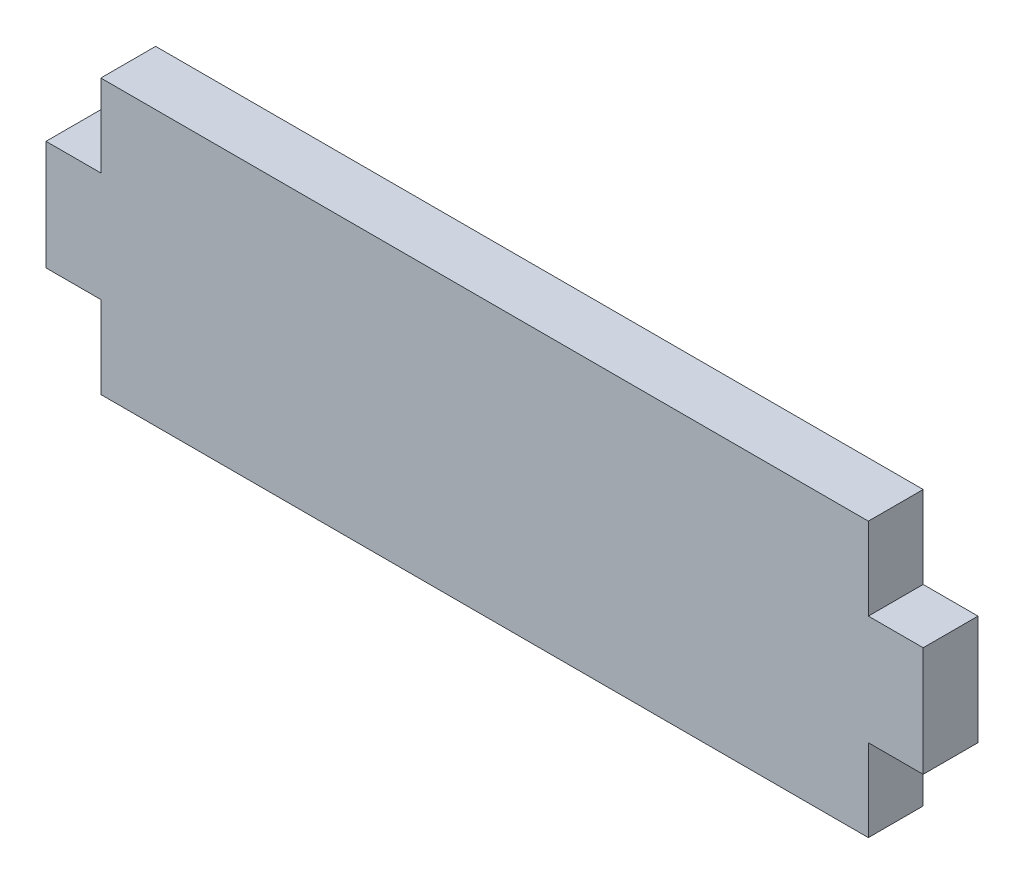
SolidWorks part; units mm, degrees
material "아크릴(내충격성)"
ref_plane "정면" through (0, 0, 0) normal (0, 0, 1) x (1, 0, 0)
ref_plane "윗면" through (0, 0, 0) normal (0, 1, 0) x (1, 0, 0)
ref_plane "우측면" through (0, 0, 0) normal (1, 0, 0) x (0, 0, -1)
sketch "스케치1" plane through (0, 0, 0) normal (0, 0, 1) x (1, 0, 0)
  line L0 (-40, 5) -> (-40, -5)
  line L1 (-35, 12.5) -> (35, 12.5)
  line L2 (-35, 12.5) -> (-35, 5)
  line L3 (-35, -12.5) -> (35, -12.5)
  line L4 (35, 12.5) -> (35, 5)
  line L5 (-35, 12.5) -> (35, -12.5) construction
  line L6 (-35, -12.5) -> (35, 12.5) construction
  line L7 (-35, -5) -> (-35, -12.5)
  line L9 (-40, 5) -> (-35, 5)
  line L10 (-40, -5) -> (-35, -5)
  line L11 (40, -5) -> (35, -5)
  line L12 (40, 5) -> (40, -5)
  line L13 (40, 5) -> (35, 5)
  line L14 (35, -5) -> (35, -12.5)
  point P0 (0, 0)
  dimension "D1" = 70
  dimension "D2" = 25
extrude "보스-돌출1" add sketch "스케치1" along normal blind 5
